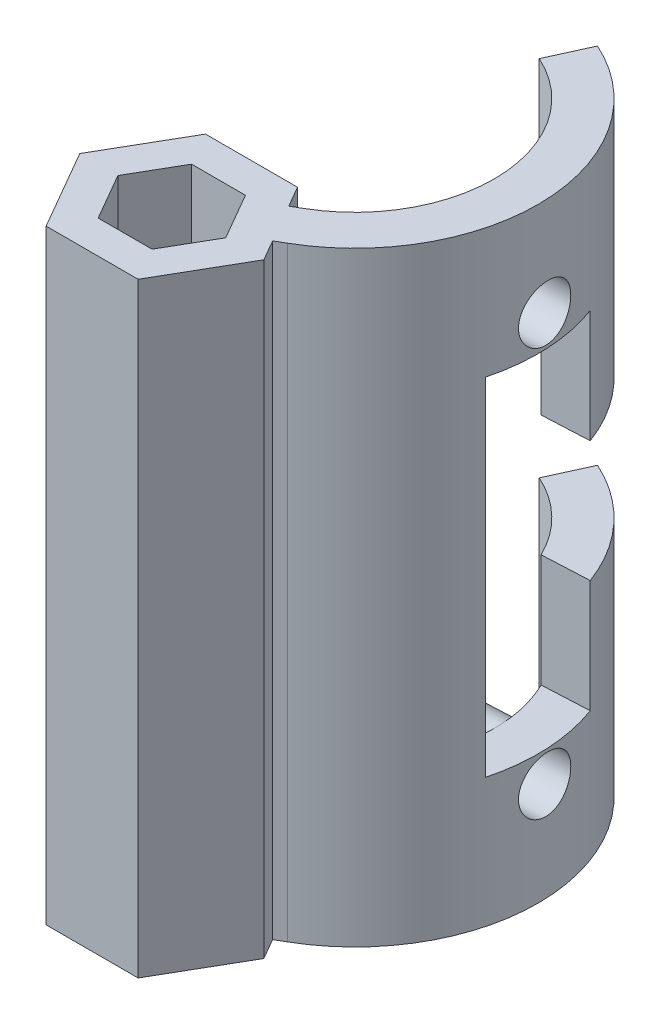
SolidWorks part; units mm, degrees
ref_plane "Front Plane" through (0, 0, 0) normal (0, 0, 1) x (1, 0, 0)
ref_plane "Top Plane" through (0, 0, 0) normal (0, 1, 0) x (1, 0, 0)
ref_plane "Right Plane" through (0, 0, 0) normal (1, 0, 0) x (0, 0, -1)
sketch "Sketch1" plane through (0, 0, 0) normal (0, 1, 0) x (1, 0, 0)
  line L0 (0, 0) -> (4.9, 0) construction
  line L1 (-4.9, 0) -> (-2.45, -4.2435)
  line L2 (-2.45, -4.2435) -> (2.45, -4.2435)
  line L3 (2.45, -4.2435) -> (4.9, 0)
  line L4 (4.9, 0) -> (2.45, 4.2435)
  line L5 (2.45, 4.2435) -> (-2.45, 4.2435)
  line L6 (-2.45, 4.2435) -> (-4.9, 0)
  line L7 (-4.1821, 7.2435) -> (-8.3641, 0)
  line L8 (-8.3641, 0) -> (-4.1821, -7.2435)
  line L9 (-4.1821, -7.2435) -> (4.1821, -7.2435)
  line L10 (4.1821, -7.2435) -> (8.3641, 0)
  line L11 (8.3641, 0) -> (4.1821, 7.2435)
  line L12 (4.1821, 7.2435) -> (-4.1821, 7.2435)
  circle A0 centre (0, 0) radius 4.2435 construction
  dimension "D1" = 4.9
  dimension "D2" = 3
extrude "Boss-Extrude1" add sketch "Sketch1" along normal blind 55
sketch "Sketch2" plane through (6.2731, 0, -3.6218) normal (0.866, 0, -0.5) x (-0.5, 0, -0.866)
  line L0 (0, 55) -> (0, 0) construction
  line L1 (-4.1821, 55) -> (4.1821, 55) construction
  line L2 (-4.1821, 0) -> (4.1821, 0) construction
  line L3 (-2, 0) -> (2, 0)
  line L4 (-2, 0) -> (-2, 55)
  line L5 (-2, 55) -> (2, 55)
  line L6 (2, 0) -> (2, 55)
  dimension "D1" = 4
sketch "Sketch3" plane through (0, 55, 0) normal (0, 1, 0) x (1, 0, 0)
  line L0 (6.2731, 3.6218) -> (7.1391, 4.1218)
  line L1 (7.2731, 1.8897) -> (5.2731, 5.3538) construction
  line L2 (7.1391, 4.1218) -> (23.5936, 13.6218) construction
  line L3 (-4.1821, -7.2435) -> (4.1821, 7.2435) construction
  line L4 (8.3641, 0) -> (4.1821, 7.2435) construction
  line L5 (4.1821, 7.2435) -> (13.1821, 22.832) construction
  arc A0 (7.1391, 4.1218) -> (13.1821, 22.832) centre (-0.1926, 16.8207) ccw
  arc A1 (13.1821, 22.832) -> (5.8723, 30.1711) centre (-0.1926, 16.8207) ccw
  dimension "D1" = 1
  dimension "D2" = 18
  dimension "D3" = 10
sweep "Sweep1" add profiles "Sketch2" path "Sketch3"
ref_plane "Plane1" through (8.8712, 0, -5.1218) normal (0.866, 0, -0.5) x (-0.5, 0, -0.866)
ref_plane "Plane2" through (0.0623, 0, -0.003) normal (-0.9988, 0, 0.0486) x (0.0486, 0, 0.9988)
ref_plane "Plane3" through (17.2677, 0, -0.8397) normal (0.9988, 0, -0.0486) x (-0.0486, 0, -0.9988)
sketch "Sketch6" plane through (17.2677, 0, -0.8397) normal (0.9988, 0, -0.0486) x (-0.0486, 0, -0.9988)
  line L0 (16.8102, 55) -> (16.8102, 0) construction
  line L2 (1.9916, 0) -> (31.6289, 0) construction
  line L3 (16.8102, 27.5) -> (9.9804, 27.5) construction
  line L5 (31.6289, 55) -> (1.9916, 55) construction
  circle A0 centre (16.8102, 46.05) radius 2.5
  circle A1 centre (16.8102, 8.95) radius 2.5
  dimension "D2" = 5
  dimension "D1" = 37.1
extrude "Cut-Extrude1" cut sketch "Sketch6" against normal blind 10
sketch "Sketch7" plane through (17.2677, 0, -0.8397) normal (0.9988, 0, -0.0486) x (-0.0486, 0, -0.9988)
  line L0 (16.8102, 8.95) -> (16.8102, 46.05) construction
  line L1 (16.8102, 27.5) -> (23.9219, 27.5) construction
  line L3 (11.8102, 43.25) -> (21.8102, 43.25)
  line L4 (11.8102, 43.25) -> (11.8102, 11.75)
  line L5 (11.8102, 11.75) -> (21.8102, 11.75)
  line L6 (21.8102, 43.25) -> (21.8102, 11.75)
  circle A0 centre (16.8102, 8.95) radius 2.5 construction
  circle A1 centre (16.8102, 46.05) radius 2.5 construction
  dimension "D2" = 10
  dimension "D1" = 31.5
extrude "Cut-Extrude2" cut sketch "Sketch7" against normal blind 10
sketch "Sketch8" plane through (17.2677, 0, -0.8397) normal (0.9988, 0, -0.0486) x (-0.0486, 0, -0.9988)
  line L0 (21.8102, 27.5) -> (29.0333, 27.5) construction
  line L1 (21.8102, 11.75) -> (21.8102, 43.25) construction
  line L2 (31.6289, 55) -> (31.6289, 0) construction
  line L3 (21.8102, 33) -> (31.6289, 33)
  line L4 (21.8102, 33) -> (21.8102, 22)
  line L5 (21.8102, 22) -> (31.6289, 22)
  line L6 (31.6289, 33) -> (31.6289, 22)
  dimension "D1" = 11
extrude "Cut-Extrude3" cut sketch "Sketch8" against normal through all
sketch "Sketch9" plane through (17.2677, 0, -0.8397) normal (0.9988, 0, -0.0486) x (-0.0486, 0, -0.9988)
  line L0 (11.8102, 27.5) -> (20.6989, 27.5) construction
  line L1 (11.8102, 43.25) -> (11.8102, 11.75) construction
  line L2 (11.8102, 43.25) -> (21.8102, 43.25) construction
  circle A0 centre (16.8102, 8.95) radius 1.7
  circle A1 centre (16.8102, 46.05) radius 1.7
  circle A2 centre (16.8102, 46.05) radius 2.8
  circle A3 centre (16.8102, 8.95) radius 2.8
  dimension "D1" = 3.4
extrude "Boss-Extrude2" add sketch "Sketch9" against normal blind 7 from offset 3.6
